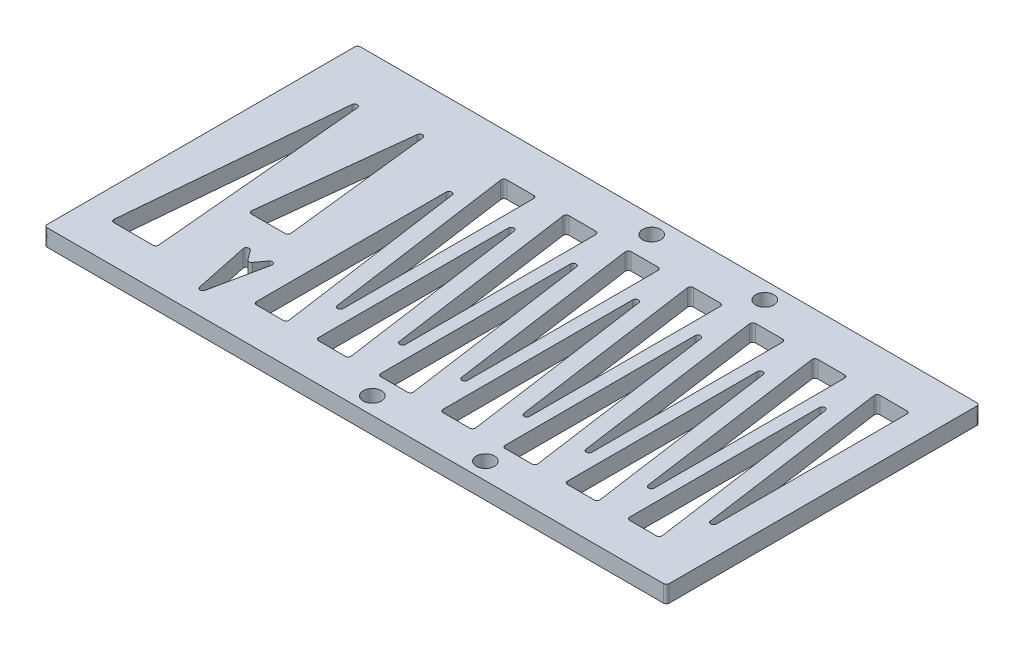
SolidWorks part; units mm, degrees
material "Hexcel AS4C (3000 丝)"
ref_plane "前视基准面" through (0, 0, 0) normal (0, 0, 1) x (1, 0, 0)
ref_plane "上视基准面" through (0, 0, 0) normal (0, 1, 0) x (1, 0, 0)
ref_plane "右视基准面" through (0, 0, 0) normal (1, 0, 0) x (0, 0, -1)
sketch "草图1" plane through (0, 0, 0) normal (0, 1, 0) x (1, 0, 0)
  line L1 (-55, 27.7) -> (-43.5, 27.7)
  line L2 (-55, 27.7) -> (-55, -27.7)
  line L3 (-55, -27.7) -> (-43.5, -27.7)
  line L4 (55, 27.7) -> (55, -27.7)
  line L5 (-55, 27.7) -> (55, -27.7) construction
  line L6 (-55, -27.7) -> (55, 27.7) construction
  line L9 (0, 0) -> (0, -20.5229) construction
  line L13 (-33.5, -27.7) -> (33.5, -27.7)
  line L14 (43.5, -27.7) -> (55, -27.7)
  line L15 (0, 0) -> (40.3011, 0) construction
  line L22 (43.5, 27.7) -> (55, 27.7)
  line L23 (-33.5, 27.7) -> (33.5, 27.7)
  line L24 (-43.5, 27.7) -> (-33.5, 27.7)
  line L25 (33.5, 27.7) -> (43.5, 27.7)
  line L26 (33.5, -27.7) -> (43.5, -27.7)
  line L27 (-43.5, -27.7) -> (-33.5, -27.7)
  point P0 (0, 0)
  dimension "D4" = 110
  dimension "D5" = 55.4
extrude "凸台-拉伸1" add sketch "草图1" along normal blind 3
sketch "草图2" plane through (0, 3, 0) normal (0, 1, 0) x (1, 0, 0)
  line L3 (0, 0) -> (0, 27.7) construction
  line L13 (0, 24.7) -> (20, 24.7) construction
  line L17 (55, 27.7) -> (-55, 27.7) construction
  line L19 (0, 0) -> (55, 0) construction
  line L20 (55, -27.7) -> (55, 27.7) construction
  circle A0 centre (0, 24.7) radius 1.6
  circle A1 centre (20, 24.7) radius 1.6
  circle A2 centre (20, -24.7) radius 1.6
  circle A3 centre (0, -24.7) radius 1.6
  dimension "D1" = 3
  dimension "D2" = 3.2
  dimension "D3" = 20
  dimension "D4" = 0
extrude "切除-拉伸1" cut sketch "草图2" against normal through all
sketch "草图4" plane through (0, 0, 0) normal (0, -1, 0) x (1, 0, 0)
  line L0 (-31.4435, 25.6686) -> (-34.4435, 11.3326)
  line L2 (-28.4435, 11.3326) -> (-31.4435, 25.6686)
  line L3 (-31.4435, 11.3326) -> (-31.4435, 25.6686) construction
  line L4 (-34.4435, 11.3326) -> (-31.4435, 15.4199)
  line L5 (-31.4435, 15.4199) -> (-28.4435, 11.3326)
  dimension "D1" = 6
extrude "切除-拉伸2" cut sketch "草图4" against normal through all
sketch "草图5" plane through (0, 0, 0) normal (0, -1, 0) x (1, 0, 0)
  line L0 (-49.9249, 21.0241) -> (-41.9323, 21.0241)
  line L1 (-41.9323, 21.0241) -> (-45.9286, -23.6883)
  line L2 (-45.9286, -23.6883) -> (-49.9249, 21.0241)
  line L3 (-39.0842, 7.5463) -> (-32.0235, 7.5463)
  line L4 (-32.0235, 7.5463) -> (-35.5539, -23.6883)
  line L5 (-35.5539, -23.6883) -> (-39.0842, 7.5463)
  line L6 (-24.6858, 21.0241) -> (-18.8711, 21.0241)
  line L7 (-18.8711, 21.0241) -> (-24.6858, -20.1429)
  line L8 (-24.6858, -20.1429) -> (-24.6858, 21.0241)
  line L9 (-15.9449, 21.0241) -> (-21.7785, -20.276)
  line L10 (-21.7785, -20.276) -> (-15.9449, -20.276)
  line L11 (-15.9449, -20.276) -> (-15.9449, 21.0241)
  line L12 (-13.6858, -20.1429) -> (-13.6858, 21.0241)
  line L13 (-13.6858, 21.0241) -> (-7.8711, 21.0241)
  line L14 (-7.8711, 21.0241) -> (-13.6858, -20.1429)
  line L15 (-4.9449, -20.276) -> (-4.9449, 21.0241)
  line L16 (-4.9449, 21.0241) -> (-10.7785, -20.276)
  line L17 (-10.7785, -20.276) -> (-4.9449, -20.276)
  line L18 (-2.6858, -20.1429) -> (-2.6858, 21.0241)
  line L19 (-2.6858, 21.0241) -> (3.1289, 21.0241)
  line L20 (3.1289, 21.0241) -> (-2.6858, -20.1429)
  line L21 (6.0551, -20.276) -> (6.0551, 21.0241)
  line L22 (6.0551, 21.0241) -> (0.2215, -20.276)
  line L23 (0.2215, -20.276) -> (6.0551, -20.276)
  line L24 (8.3142, -20.1429) -> (8.3142, 21.0241)
  line L25 (8.3142, 21.0241) -> (14.1289, 21.0241)
  line L26 (14.1289, 21.0241) -> (8.3142, -20.1429)
  line L27 (17.0551, -20.276) -> (17.0551, 21.0241)
  line L28 (17.0551, 21.0241) -> (11.2215, -20.276)
  line L29 (11.2215, -20.276) -> (17.0551, -20.276)
  line L30 (19.3142, -20.1429) -> (19.3142, 21.0241)
  line L31 (19.3142, 21.0241) -> (25.1289, 21.0241)
  line L32 (25.1289, 21.0241) -> (19.3142, -20.1429)
  line L33 (28.0551, -20.276) -> (28.0551, 21.0241)
  line L34 (28.0551, 21.0241) -> (22.2215, -20.276)
  line L35 (22.2215, -20.276) -> (28.0551, -20.276)
  line L36 (30.3142, -20.1429) -> (30.3142, 21.0241)
  line L37 (30.3142, 21.0241) -> (36.1289, 21.0241)
  line L38 (36.1289, 21.0241) -> (30.3142, -20.1429)
  line L39 (39.0551, -20.276) -> (39.0551, 21.0241)
  line L40 (39.0551, 21.0241) -> (33.2215, -20.276)
  line L41 (33.2215, -20.276) -> (39.0551, -20.276)
  line L42 (41.3142, -20.1429) -> (41.3142, 21.0241)
  line L43 (41.3142, 21.0241) -> (47.1289, 21.0241)
  line L44 (47.1289, 21.0241) -> (41.3142, -20.1429)
  line L45 (50.0551, -20.276) -> (50.0551, 21.0241)
  line L46 (50.0551, 21.0241) -> (44.2215, -20.276)
  line L47 (44.2215, -20.276) -> (50.0551, -20.276)
extrude "切除-拉伸3" cut sketch "草图5" against normal through all
fillet "圆角2" radius 0.5 56 edges at (-55, 1.5, 27.7) (-55, 1.5, -27.7) (55, 1.5, -27.7) (55, 1.5, 27.7) (-31.4435, 1.5, 25.6686) (-28.4435, 1.5, 11.3326) (-4.9449, 1.5, -20.276) (-10.7785, 1.5, -20.276) (-4.9449, 1.5, 21.0241) (-2.6858, 1.5, -20.1429) (-2.6858, 1.5, 21.0241) (3.1289, 1.5, 21.0241) (6.0551, 1.5, -20.276) (0.2215, 1.5, -20.276) (6.0551, 1.5, 21.0241) (8.3142, 1.5, -20.1429) (8.3142, 1.5, 21.0241) (14.1289, 1.5, 21.0241) (-32.0235, 1.5, 7.5463) (-35.5539, 1.5, -23.6883) (-39.0842, 1.5, 7.5463) (-18.8711, 1.5, 21.0241) (-24.6858, 1.5, -20.1429) (-24.6858, 1.5, 21.0241) (-21.7785, 1.5, -20.276) (-15.9449, 1.5, 21.0241) (-15.9449, 1.5, -20.276) (-13.6858, 1.5, -20.1429) (-13.6858, 1.5, 21.0241) (-7.8711, 1.5, 21.0241) (39.0551, 1.5, -20.276) (33.2215, 1.5, -20.276) (39.0551, 1.5, 21.0241) (41.3142, 1.5, -20.1429) (41.3142, 1.5, 21.0241) (47.1289, 1.5, 21.0241) (50.0551, 1.5, -20.276) (44.2215, 1.5, -20.276) (50.0551, 1.5, 21.0241) (17.0551, 1.5, -20.276) (11.2215, 1.5, -20.276) (17.0551, 1.5, 21.0241) (19.3142, 1.5, -20.1429) (19.3142, 1.5, 21.0241) (25.1289, 1.5, 21.0241) (28.0551, 1.5, -20.276) (22.2215, 1.5, -20.276) (28.0551, 1.5, 21.0241) (30.3142, 1.5, -20.1429) (30.3142, 1.5, 21.0241) (36.1289, 1.5, 21.0241) (-41.9323, 1.5, 21.0241) (-49.9249, 1.5, 21.0241) (-45.9286, 1.5, -23.6883) (-34.4435, 1.5, 11.3326) (-31.4435, 1.5, 15.4199)
